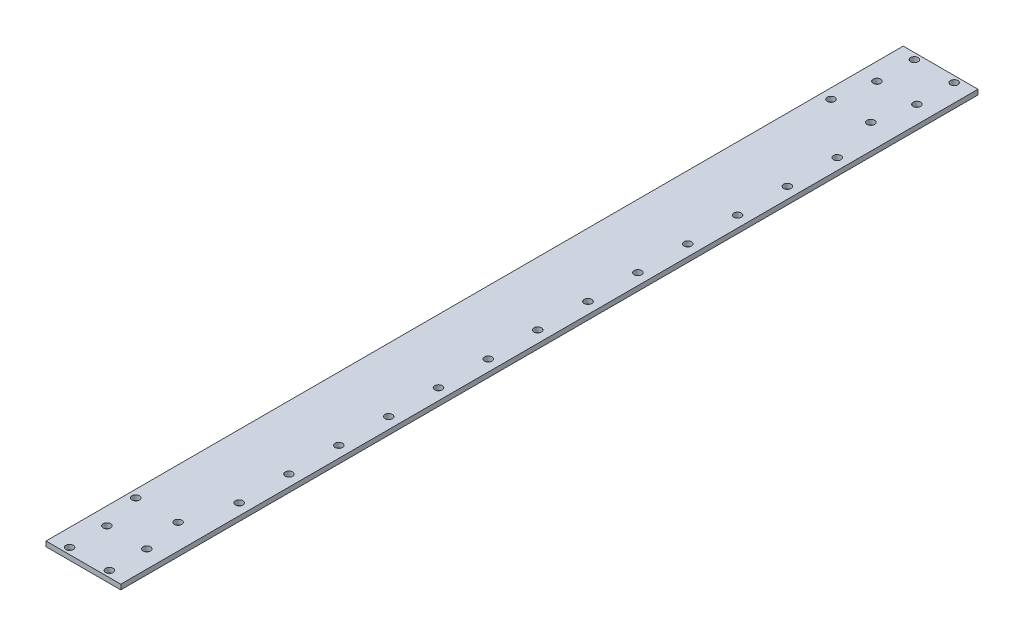
SolidWorks part; units mm, degrees
ref_plane "Front Plane" through (0, 0, 0) normal (0, 0, 1) x (1, 0, 0)
ref_plane "Top Plane" through (0, 0, 0) normal (0, 1, 0) x (1, 0, 0)
ref_plane "Right Plane" through (0, 0, 0) normal (1, 0, 0) x (0, 0, -1)
sketch "Sketch1" plane through (0, 0, 0) normal (0, 0, 1) x (1, 0, 0)
  line L1 (15, -1) -> (-15, -1)
  line L2 (15, -1) -> (15, 1)
  line L3 (15, 1) -> (-15, 1)
  line L4 (-15, -1) -> (-15, 1)
  line L5 (15, -1) -> (-15, 1) construction
  line L6 (15, 1) -> (-15, -1) construction
  point P0 (0, 0)
extrude "Boss-Extrude1" add sketch "Sketch1" along normal blind 200 and the other way up to surface (144 mm away)
hole_wizard "Ø3.0 (3) Diameter Slot1" positions "Sketch4" profile "Sketch5" size "Ø3.0" standard "ISO" slot yes end condition through all
sketch "Sketch4" plane through (0, 1, 0) normal (0, 1, 0) x (1, 0, 0)
  point P0 (-8.05, 126.5)
  point P3 (7.95, 126.5)
  point P6 (7.95, 141.5)
  point P9 (-8.05, 141.5)
sketch "Sketch5" plane through (-8.05, 1, -126.5) normal (1, 0, 0) x (0, 0, 1)
  line L0 (0, 0) -> (0, 2)
  line L1 (0, 2) -> (1.5, 2)
  line L2 (1.5, 2) -> (1.5, 0)
  line L5 (1.5, 0) -> (0, 0)
  line L11 (0, -6.35) -> (0, 107.95) construction
  dimension "Thru Hole Dia." = 3
  dimension "Thru Hole Depth" = 2
hole_wizard "Ø3.0mm Dowel Hole1" positions "Sketch8" profile "Sketch9" hole size "Ø3.0" standard "ISO" end condition up to next
sketch "Sketch8" plane through (0, -1, 0) normal (0, -1, 0) x (-1, 0, 0)
  line L0 (-6, -28) -> (-14.6, -28) construction
  point P0 (-7.95, -197.5)
  point P3 (8.05, -197.5)
  point P6 (8.05, -182.5)
  point P9 (-7.95, -182.5)
  point P12 (-5, -167)
  point P15 (12, -167)
  point P18 (-10.5, -148)
  point P24 (-10.5, -128)
  point P27 (-10.5, -108)
  point P30 (-10.5, -88)
  point P33 (-10.5, -68)
  point P36 (-10.5, -48)
  point P39 (-10.3, -28)
  point P43 (-10.5, -8)
  point P46 (-10.5, 12)
  point P49 (-10.5, 32)
  point P52 (-10.5, 52)
  point P55 (-10.5, 72)
  point P58 (-10.5, 92)
  point P61 (-5, 111)
  point P68 (11, 111)
sketch "Sketch9" plane through (7.95, -1, 197.5) normal (1, 0, 0) x (0, 0, -1)
  line L0 (0, 0) -> (0, 2)
  line L1 (0, 2) -> (1.5, 2)
  line L2 (1.5, 2) -> (1.5, 0)
  line L5 (1.5, 0) -> (0, 0)
  line L11 (0, -6.35) -> (0, 107.95) construction
  dimension "Thru Hole Dia." = 3
  dimension "Thru Hole Depth" = 2
